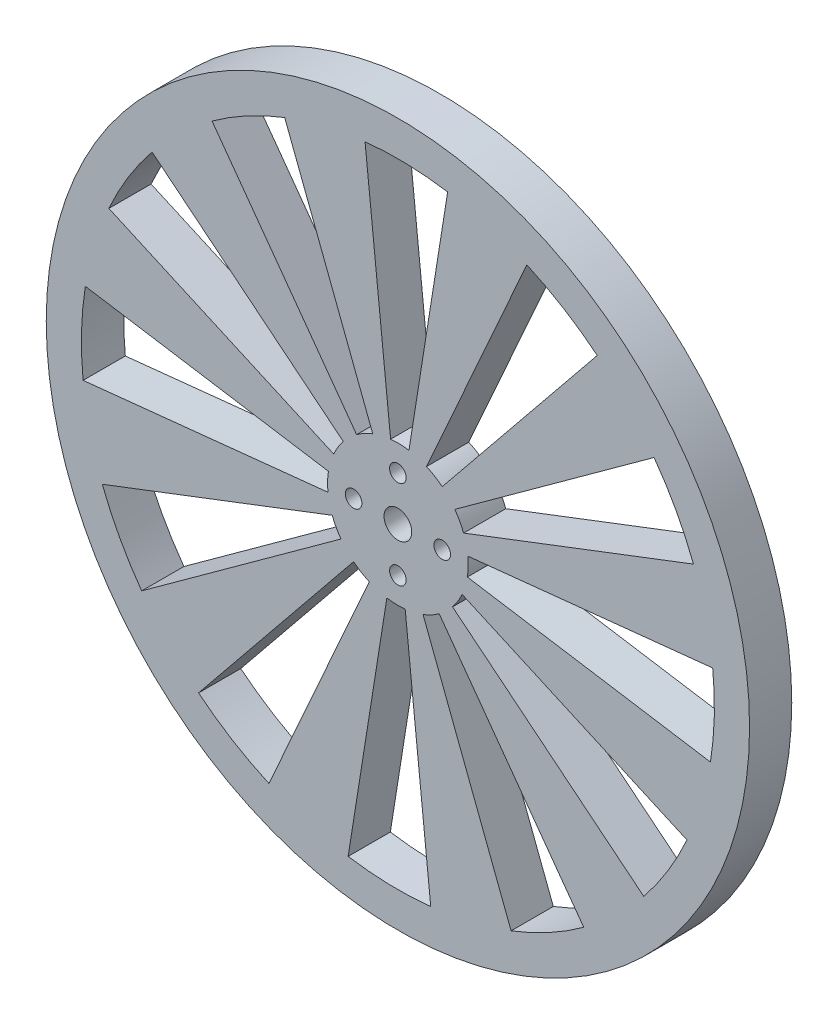
SolidWorks part; units mm, degrees
ref_plane "Front Plane" through (0, 0, 0) normal (0, 0, 1) x (1, 0, 0)
ref_plane "Top Plane" through (0, 0, 0) normal (0, 1, 0) x (1, 0, 0)
ref_plane "Right Plane" through (0, 0, 0) normal (1, 0, 0) x (0, 0, -1)
sketch "Sketch2" plane through (0, 0, 0) normal (0, 0, 1) x (1, 0, 0)
  circle A0 centre (0, 0) radius 63.5
  dimension "D1" = 127
extrude "Boss-Extrude1" add sketch "Sketch2" along normal blind 7.62
sketch "Sketch5" plane through (0, 0, 7.62) normal (0, 0, 1) x (1, 0, 0)
  line L0 (0, 0) -> (23.2839, 52.1918)
  line L1 (0, 0) -> (35.9988, 44.3871)
  line L2 (0, 0) -> (53.3694, 20.4409)
  line L3 (0, 0) -> (46.2604, 33.5574)
  line L4 (0, 0) -> (56.4397, -8.9823)
  line L5 (0, 0) -> (56.8414, 5.9314)
  line L6 (0, 0) -> (44.3871, -35.9988)
  line L7 (0, 0) -> (52.1918, -23.2839)
  line L8 (0, 0) -> (20.4409, -53.3694)
  line L9 (0, 0) -> (33.5574, -46.2604)
  line L10 (0, 0) -> (-8.9823, -56.4397)
  line L11 (0, 0) -> (5.9314, -56.8414)
  line L12 (0, 0) -> (-35.9988, -44.3871)
  line L13 (0, 0) -> (-23.2839, -52.1918)
  line L14 (0, 0) -> (-53.3694, -20.4409)
  line L15 (0, 0) -> (-46.2604, -33.5574)
  line L16 (0, 0) -> (-56.4397, 8.9823)
  line L17 (0, 0) -> (-56.8414, -5.9314)
  line L18 (0, 0) -> (-44.3871, 35.9988)
  line L19 (0, 0) -> (-52.1918, 23.2839)
  line L20 (0, 0) -> (-20.4409, 53.3694)
  line L21 (0, 0) -> (-33.5574, 46.2604)
  line L22 (0, 0) -> (8.9823, 56.4397)
  line L23 (0, 0) -> (-5.9314, 56.8414)
  circle A0 centre (0, 0) radius 12.7
  circle A1 centre (0, 0) radius 57.15
  point P30 (0, 0)
  dimension "D1" = 25.4
  dimension "D2" = 114.3
  dimension "D3" = 15
  dimension "D4" = 44.3871
  dimension "D5" = 12
extrude "Cut-Extrude3" cut sketch "Sketch5" against normal through all contours L22 A1 L23 A0 | L1 A1 L0 A0 | L2 A1 L3 A0 | L4 A1 L5 A0 | L6 A1 L7 A0 | L8 A1 L9 A0 | L10 A1 L11 A0 | L12 A1 L13 A0 | L14 A1 L15 A0 | L16 A1 L17 A0 | L18 A1 L19 A0 | L20 A1 L21 A0
sketch "Sketch6" plane through (0, 0, 7.62) normal (0, 0, 1) x (1, 0, 0)
  line L0 (1.9961, 12.5422) -> (8.9823, 56.4397) construction
  circle A8 centre (0, 8) radius 1.5
  dimension "D1" = 3
  dimension "D2" = 8
  dimension "D3" = 1.2574
extrude "Cut-Extrude6" cut sketch "Sketch6" against normal through all
pattern_circular "CirPattern1" count 4 over 360 about axis through (0, 0, 0) along (0, 0, 1) of "Cut-Extrude6"
sketch "Sketch7" plane through (0, 0, 7.62) normal (0, 0, 1) x (1, 0, 0)
  circle A0 centre (0, 0) radius 2.5
  dimension "D1" = 5
extrude "Cut-Extrude5" cut sketch "Sketch7" against normal through all
